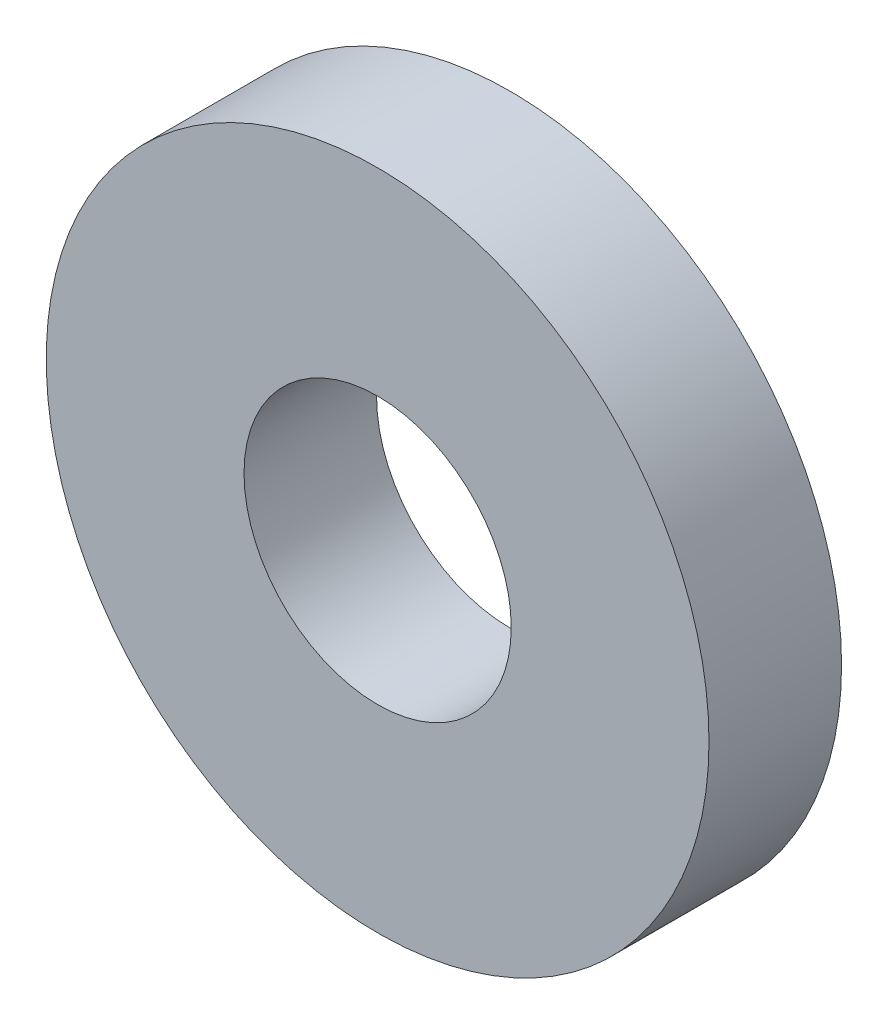
SolidWorks part; units mm, degrees
ref_plane "Front Plane" through (0, 0, 0) normal (0, 0, 1) x (1, 0, 0)
ref_plane "Top Plane" through (0, 0, 0) normal (0, 1, 0) x (1, 0, 0)
ref_plane "Right Plane" through (0, 0, 0) normal (1, 0, 0) x (0, 0, -1)
sketch "Sketch1" plane through (0, 0, 0) normal (0, 0, 1) x (1, 0, 0)
  circle A0 centre (0, 0) radius 7.9375
  circle A1 centre (0, 0) radius 3.2004
  dimension "OD" = 15.875
  dimension "ID" = 6.4008
extrude "Extrude1" add sketch "Sketch1" along normal mid plane 3.175
sketch "Sketch2" plane through (0, 0, 0) normal (1, 0, 0) x (0, 0, -1)
  line L0 (-1.5875, -3.2004) -> (1.5875, -3.2004) construction
  line L3 (1.5875, 3.2004) -> (-1.5875, 3.2004) construction
  line L5 (-1.5875, -3.2004) -> (1.5875, -3.2004)
  line L6 (1.5875, 3.2004) -> (-1.5875, 3.2004)
sketch "Sketch4" plane through (0, 0, 1.5875) normal (0, 0, 1) x (1, 0, 0)
  line L0 (0, 0) -> (-2.263, 2.263)
  line L1 (0, -2.1828) -> (0, 2.1828) construction
  circle A0 centre (0, 0) radius 3.2004 construction
  dimension "D1" = 45
